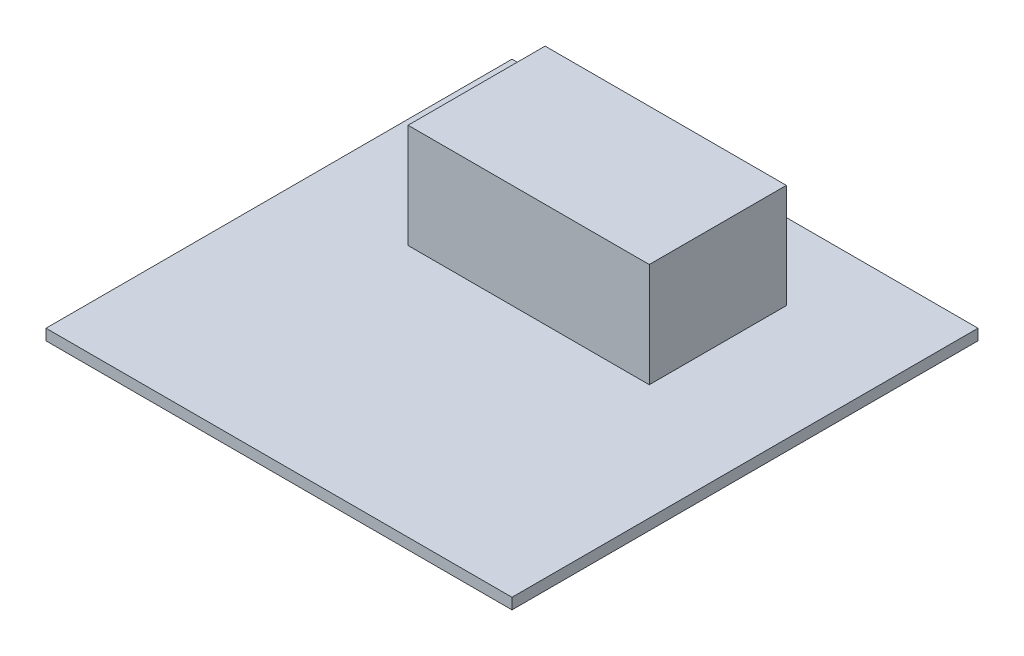
SolidWorks part; units mm, degrees
ref_plane "Front Plane" through (0, 0, 0) normal (0, 0, 1) x (1, 0, 0)
ref_plane "Top Plane" through (0, 0, 0) normal (0, 1, 0) x (1, 0, 0)
ref_plane "Right Plane" through (0, 0, 0) normal (1, 0, 0) x (0, 0, -1)
sketch "Sketch1" plane through (0, 0, 0) normal (0, 1, 0) x (1, 0, 0)
  line L1 (0, 0) -> (170, 0)
  line L2 (0, 0) -> (0, -170)
  line L3 (0, -170) -> (170, -170)
  line L4 (170, 0) -> (170, -170)
  dimension "D1" = 170
extrude "Boss-Extrude1" add sketch "Sketch1" along normal blind 4
sketch "Sketch2" plane through (0, 4, 0) normal (0, 1, 0) x (1, 0, 0)
  line L1 (39.9124, -27.8311) -> (127.9124, -27.8311)
  line L2 (39.9124, -27.8311) -> (39.9124, -77.8311)
  line L3 (39.9124, -77.8311) -> (127.9124, -77.8311)
  line L4 (127.9124, -27.8311) -> (127.9124, -77.8311)
  dimension "D1" = 88
  dimension "D2" = 50
extrude "Boss-Extrude2" add sketch "Sketch2" along normal blind 38
